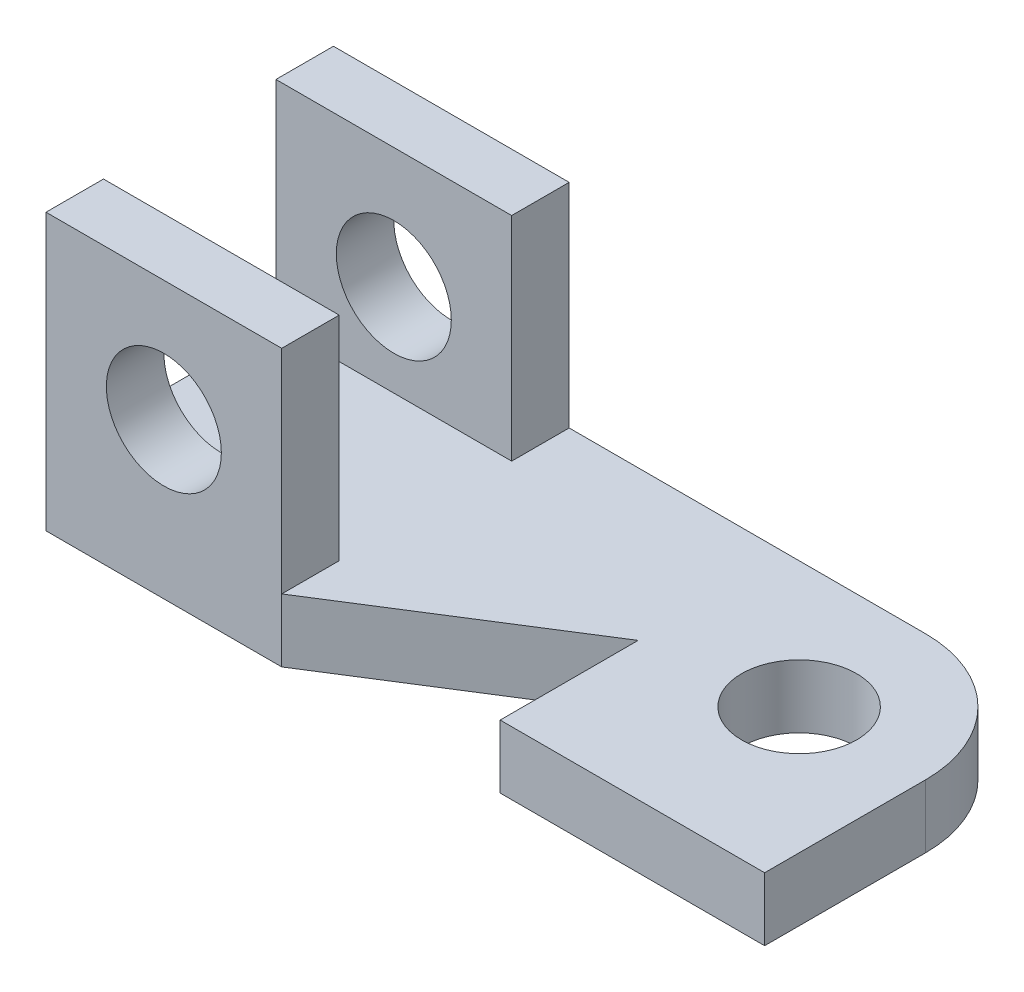
SolidWorks part; units mm, degrees
ref_plane "Front Plane" through (0, 0, 0) normal (0, 0, 1) x (1, 0, 0)
ref_plane "Top Plane" through (0, 0, 0) normal (0, 1, 0) x (1, 0, 0)
ref_plane "Right Plane" through (0, 0, 0) normal (1, 0, 0) x (0, 0, -1)
sketch "Sketch1" plane through (0, 0, 0) normal (0, 1, 0) x (1, 0, 0)
  line L0 (0, 0) -> (0, 50)
  line L1 (0, 50) -> (103, 50)
  line L2 (0, 0) -> (41, 0)
  line L3 (41, 0) -> (79, 24)
  line L4 (79, 24) -> (79, 0)
  line L5 (79, 0) -> (125, 0)
  line L6 (125, 0) -> (125, 28)
  arc A1 (103, 50) -> (125, 28) centre (103, 28) cw
  dimension "D1" = 22
  dimension "D2" = 46
  dimension "D3" = 41
  dimension "D4" = 103
  dimension "D5" = 38
  dimension "D6" = 24
  dimension "D7" = 50
extrude "Boss-Extrude1" add sketch "Sketch1" along normal blind 11
sketch "Sketch2" plane through (0, 11, 0) normal (0, 1, 0) x (1, 0, 0)
  line L0 (103, 50) -> (0, 50) construction
  line L1 (125, 0) -> (125, 28) construction
  circle A0 centre (103, 28) radius 10
  point P2 (0, 0)
  point P3 (100.7398, 24.2945)
  point P4 (91.5247, 36.5812)
  dimension "D1" = 20
  dimension "D2" = 22
  dimension "D3" = 22
extrude "Cut-Extrude1" cut sketch "Sketch2" against normal through all
sketch "Sketch4" plane through (0, 0, 0) normal (0, 1, 0) x (1, 0, 0)
  line L0 (0, 50) -> (0, 0) construction
  line L1 (0, 0) -> (41, 0)
  line L2 (0, 0) -> (0, 10)
  line L3 (0, 10) -> (41, 10)
  line L4 (41, 0) -> (41, 10)
  line L5 (0, 50) -> (41, 50)
  line L6 (0, 50) -> (0, 40)
  line L7 (0, 40) -> (41, 40)
  line L8 (41, 50) -> (41, 40)
  line L9 (103, 50) -> (0, 50) construction
  dimension "D1" = 10
  dimension "D2" = 41
extrude "Boss-Extrude2" add sketch "Sketch4" along normal blind 48
sketch "Sketch5" plane through (0, 0, 0) normal (0, 0, 1) x (1, 0, 0)
  line L0 (0, 48) -> (0, 0) construction
  line L2 (0, 48) -> (41, 48) construction
  circle A0 centre (20.5, 27) radius 10
  point P4 (20.5, 48)
  dimension "D1" = 20
  dimension "D2" = 20.5
  dimension "D3" = 21
extrude "Cut-Extrude2" cut sketch "Sketch5" against normal through all
